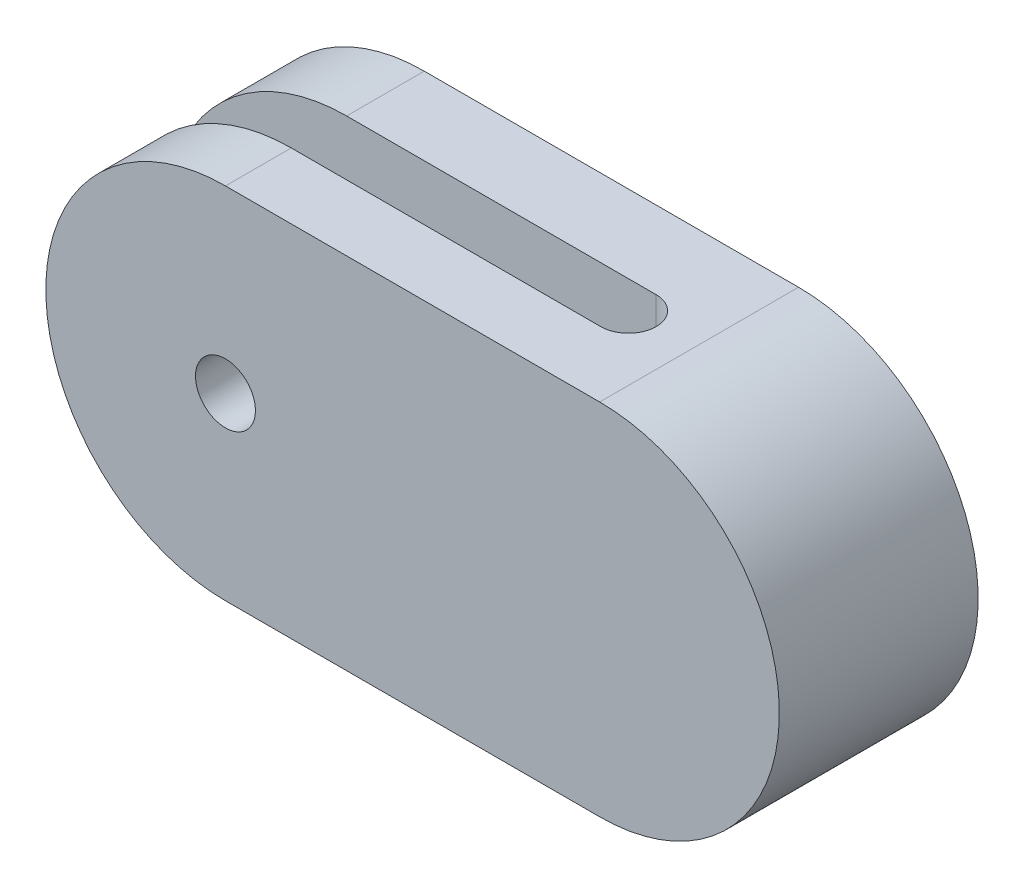
SolidWorks part; units mm, degrees
ref_plane "Front Plane" through (0, 0, 0) normal (0, 0, 1) x (1, 0, 0)
ref_plane "Top Plane" through (0, 0, 0) normal (0, 1, 0) x (1, 0, 0)
ref_plane "Right Plane" through (0, 0, 0) normal (1, 0, 0) x (0, 0, -1)
sketch "Sketch1" plane through (0, 0, 0) normal (0, 0, 1) x (1, 0, 0)
  line L0 (10.3124, -14.55) -> (22.8124, -14.55) construction
  line L1 (10.3124, -8.55) -> (22.8124, -8.55)
  line L2 (10.3124, -20.55) -> (22.8124, -20.55)
  arc A0 (10.3124, -8.55) -> (10.3124, -20.55) centre (10.3124, -14.55) ccw
  arc A1 (22.8124, -20.55) -> (22.8124, -8.55) centre (22.8124, -14.55) ccw
  point P3 (16.5624, -14.55)
  dimension "D1" = 6
  dimension "D2" = 12.5
extrude "Boss-Extrude1" add sketch "Sketch1" along normal offset from surface 0.15 and the other way offset from surface (4.293 mm away) 0.15 contours A1 L1 A0 L2
sketch "Sketch2" plane through (0, -20.55, 0) normal (0, -1, 0) x (1, 0, 0)
  line L0 (4.3124, -0.775) -> (20.65, -0.775) construction
  line L1 (20.65, 0) -> (20.65, -1.55) construction
  line L2 (4.3124, 0.15) -> (20.65, 0.15)
  line L3 (4.3124, -1.7) -> (20.65, -1.7)
  line L4 (17.65, 0) -> (-17.65, 0) construction
  line L5 (4.3124, 2.3476) -> (4.3124, -4.293) construction
  arc A0 (4.3124, 0.15) -> (4.3124, -1.7) centre (4.3124, -0.775) ccw
  arc A1 (20.65, -1.7) -> (20.65, 0.15) centre (20.65, -0.775) ccw
  point P4 (12.4812, -0.775)
  dimension "D1" = 0.15
extrude "Cut-Extrude1" cut sketch "Sketch2" against normal through all
sketch "Sketch3" plane through (0, 0, -4.293) normal (0, 0, -1) x (-1, 0, 0)
  circle A0 centre (-10.3124, -14.55) radius 1.575
  dimension "D1" = 3.15
extrude "Cut-Extrude2" cut sketch "Sketch3" against normal up to surface (2.593 mm away) up to face at (13.9812, -14.55, -1.7)
sketch "Sketch4" plane through (0, 0, 0.15) normal (0, 0, -1) x (-1, 0, 0)
  circle A0 centre (-10.3124, -14.55) radius 1
  dimension "D1" = 2
extrude "Cut-Extrude3" cut sketch "Sketch4" against normal through all
